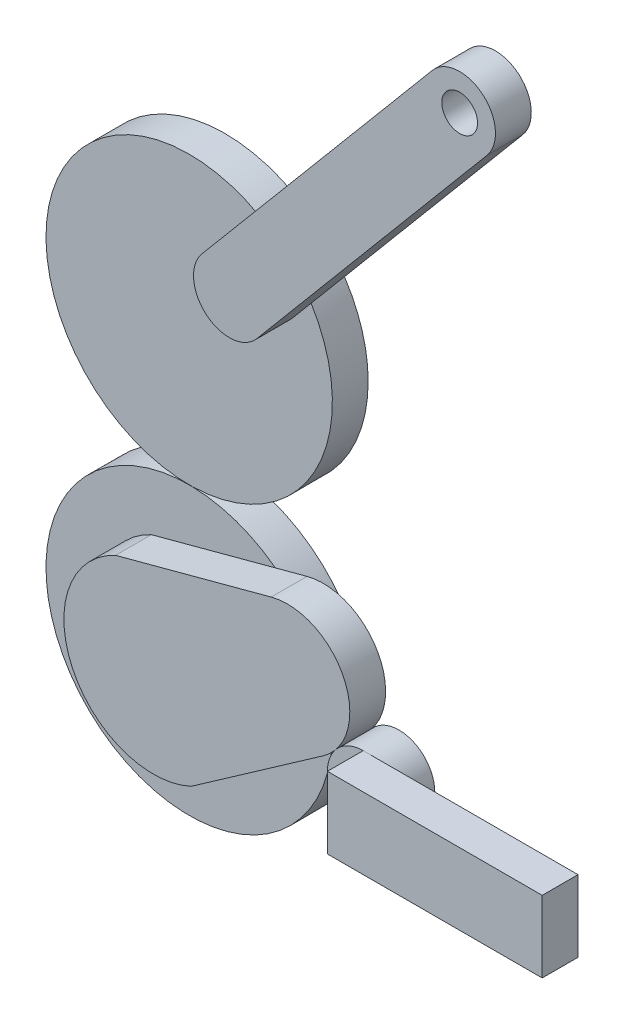
SolidWorks part; units mm, degrees
ref_plane "前视基准面" through (0, 0, 0) normal (0, 0, 1) x (1, 0, 0)
ref_plane "上视基准面" through (0, 0, 0) normal (0, 1, 0) x (1, 0, 0)
ref_plane "右视基准面" through (0, 0, 0) normal (1, 0, 0) x (0, 0, -1)
sketch "草图1" plane through (0, 0, 0) normal (0, 0, 1) x (1, 0, 0)
  line L0 (0, 88.6781) -> (0, -130.0364) construction
  circle A0 centre (0, 0) radius 40
  circle A1 centre (0, -80) radius 40
  dimension "D1" = 80
  dimension "D2" = 80
extrude "凸台-拉伸1" add sketch "草图1" along normal blind 10 contours A0
sketch "草图2" plane through (0, 0, 0) normal (0, 0, 1) x (1, 0, 0)
  line L0 (0, 51.5776) -> (0, -115.0476) construction
  circle A0 centre (0, -80) radius 40
  circle A1 centre (0, 0) radius 40 construction
  dimension "D1" = 80
extrude "凸台-拉伸2" add sketch "草图2" along normal blind 10 separate body
sketch "草图3" plane through (0, 0, 10) normal (0, 0, 1) x (1, 0, 0)
  line L0 (-49.8893, -80) -> (73.6733, -80) construction
  line L1 (0, -129.5009) -> (0, -43.5196) construction
  line L2 (-10.5655, -57.3423) -> (32.9012, -45.6954)
  line L3 (-10.5655, -57.3423) -> (10.5655, -102.6577) construction
  line L4 (-22.6577, -90.5655) -> (29.4261, -66.2784) construction
  line L5 (10.5655, -102.6577) -> (47.4273, -76.8468)
  arc A0 (10.5655, -102.6577) -> (-10.5655, -57.3423) centre (0, -80) cw
  arc A2 (47.4273, -76.8468) -> (32.9012, -45.6954) centre (37.4178, -62.5518) ccw
  point P14 (0, 0)
  dimension "D1" = 25
  dimension "D4" = 17.451
  dimension "D5" = 25
  dimension "D6" = 80
  dimension "D2" = 80
  dimension "D3" = 45
extrude "凸台-拉伸3" add sketch "草图3" along normal blind 10
sketch "草图4" plane through (0, 0, 0) normal (0, 0, 1) x (1, 0, 0)
  line L0 (0, -80) -> (116.6953, -80) construction
  circle A0 centre (58.6102, -80) radius 10
  arc A1 (47.4273, -76.8468) -> (32.9012, -45.6954) centre (37.4178, -62.5518) ccw construction
  dimension "D1" = 20
extrude "凸台-拉伸4" add sketch "草图4" along normal blind 10 from offset 10 separate body
sketch "草图5" plane through (0, 0, 20) normal (0, 0, 1) x (1, 0, 0)
  line L0 (58.6102, -70) -> (58.6102, -90)
  line L1 (58.6102, -90) -> (118.6102, -90)
  line L2 (118.6102, -90) -> (118.6102, -70)
  line L3 (118.6102, -70) -> (58.6102, -70)
  circle A0 centre (58.6102, -80) radius 10 construction
  dimension "D1" = 60
  dimension "D2" = 20
extrude "凸台-拉伸5" add sketch "草图5" along normal blind 10
sketch "草图6" plane through (0, 0, 10) normal (0, 0, 1) x (1, 0, 0)
  line L0 (0, 0) -> (40, 0) construction
  line L1 (0, 0) -> (21.2132, 21.2132) construction
  circle A0 centre (0, 0) radius 40 construction
  circle A1 centre (21.2132, 21.2132) radius 5
  dimension "D3" = 10
  dimension "D1" = 45
  dimension "D2" = 30
extrude "切除-拉伸1" cut sketch "草图6" against normal blind 10
sketch "草图7" plane through (0, 0, 10) normal (0, 0, 1) x (1, 0, 0)
  line L0 (13.5582, 27.6476) -> (77.9017, 104.1976)
  line L1 (28.8682, 14.7789) -> (93.2117, 91.3289)
  arc A0 (13.5582, 27.6476) -> (28.8682, 14.7789) centre (21.2132, 21.2132) ccw
  arc A2 (93.2117, 91.3289) -> (77.9017, 104.1976) centre (85.5567, 97.7633) ccw
  dimension "D1" = 10
  dimension "D2" = 100
  dimension "D3" = 100
extrude "凸台-拉伸6" add sketch "草图7" along normal blind 10
sketch "草图8" plane through (0, 0, 20) normal (0, 0, 1) x (1, 0, 0)
  circle A0 centre (85.5567, 97.7633) radius 5
  dimension "D1" = 10
extrude "切除-拉伸2" cut sketch "草图8" against normal blind 10
